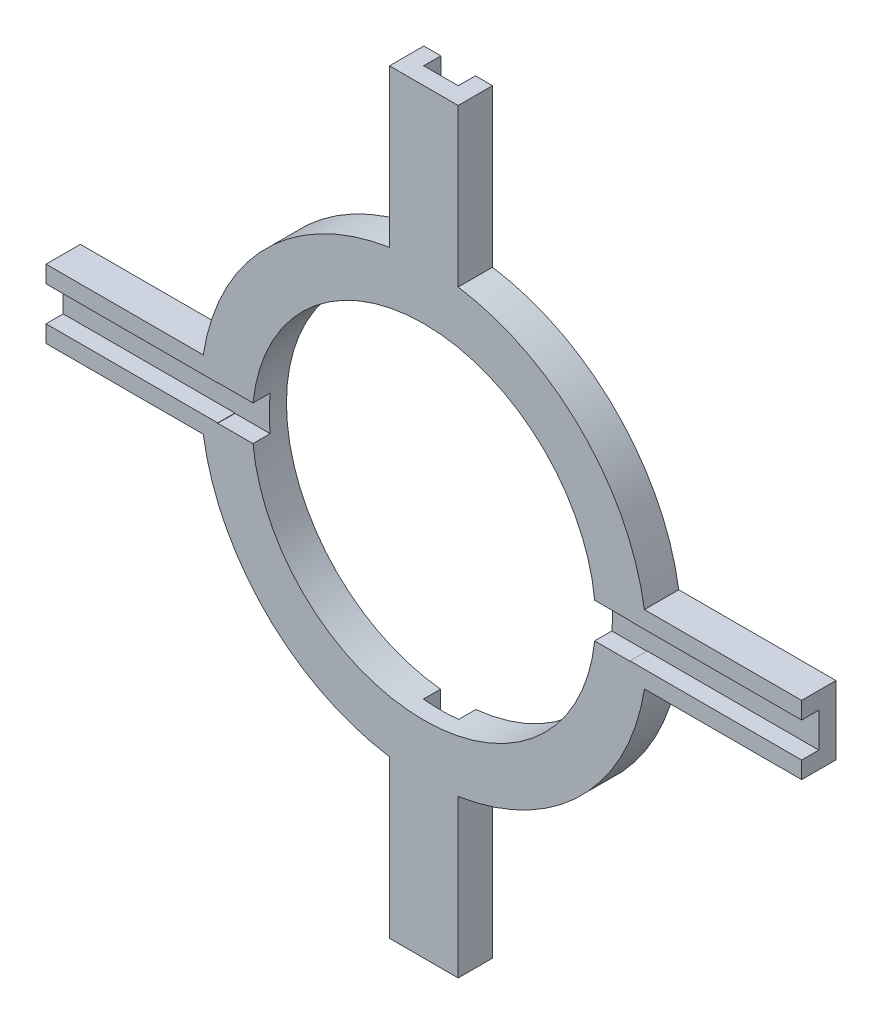
SolidWorks part; units mm, degrees
material "POM Acetal Copolymer"
ref_plane "Front Plane" through (0, 0, 0) normal (0, 0, 1) x (1, 0, 0)
ref_plane "Top Plane" through (0, 0, 0) normal (0, 1, 0) x (1, 0, 0)
ref_plane "Right Plane" through (0, 0, 0) normal (1, 0, 0) x (0, 0, -1)
sketch "Sketch1" plane through (0, 0, 0) normal (0, 0, 1) x (1, 0, 0)
  circle A0 centre (0, 0) radius 26
  circle A1 centre (0, 0) radius 20
extrude "Relieved_Floating_Ring" add sketch "Sketch1" along normal blind 4
sketch "Sketch2" plane through (0, 0, 0) normal (0, 0, 1) x (1, 0, 0)
  line L1 (-44, -4) -> (-24, -4)
  line L2 (-44, -4) -> (-44, 4)
  line L3 (-44, 4) -> (-24, 4)
  line L4 (-24, -4) -> (-24, 4)
extrude "X_Slide_Pad_-1" add sketch "Sketch2" along normal blind 4
sketch "Sketch3" plane through (0, 0, 0) normal (0, 0, 1) x (1, 0, 0)
  line L1 (-4, -44) -> (4, -44)
  line L2 (-4, -44) -> (-4, -24)
  line L3 (-4, -24) -> (4, -24)
  line L4 (4, -44) -> (4, -24)
extrude "Y_Slide_Pad_-1" add sketch "Sketch3" along normal blind 4
sketch "Sketch4" plane through (0, 0, 0) normal (0, 0, 1) x (1, 0, 0)
  line L1 (24, -4) -> (44, -4)
  line L2 (24, -4) -> (24, 4)
  line L3 (24, 4) -> (44, 4)
  line L4 (44, -4) -> (44, 4)
extrude "X_Slide_Pad_1" add sketch "Sketch4" along normal blind 4
sketch "Sketch5" plane through (0, 0, 0) normal (0, 0, 1) x (1, 0, 0)
  line L1 (-4, 24) -> (4, 24)
  line L2 (-4, 24) -> (-4, 44)
  line L3 (-4, 44) -> (4, 44)
  line L4 (4, 24) -> (4, 44)
extrude "Y_Slide_Pad_1" add sketch "Sketch5" along normal blind 4
sketch "Sketch6" plane through (0, 0, 0) normal (0, 0, -1) x (-1, 0, 0)
  line L0 (2.05, -45) -> (-2.05, -45)
  line L1 (-2.05, -45) -> (-2.05, 45)
  line L2 (-2.05, 45) -> (2.05, 45)
  line L3 (2.05, 45) -> (2.05, -45)
extrude "Lower_Y_Slots_W4p1_H2" cut sketch "Sketch6" against normal blind 2
sketch "Sketch7" plane through (0, 0, 4) normal (0, 0, 1) x (1, 0, 0)
  line L0 (-45, -2.05) -> (45, -2.05)
  line L1 (45, -2.05) -> (45, 2.05)
  line L2 (45, 2.05) -> (-45, 2.05)
  line L3 (-45, 2.05) -> (-45, -2.05)
extrude "Upper_X_Slots_W4p1_H2" cut sketch "Sketch7" against normal blind 2
sketch "Sketch8" plane through (0, 0, 0) normal (0, 0, 1) x (1, 0, 0)
  line L1 (-44, -2.06) -> (-24, -2.06)
  line L2 (-44, -2.06) -> (-44, -2.015)
  line L3 (-44, -2.015) -> (-24, -2.015)
  line L4 (-24, -2.06) -> (-24, -2.015)
extrude "Bench_UpperX_W4p030_-1_-1" add sketch "Sketch8" along normal blind 2 from offset 2
sketch "Sketch9" plane through (0, 0, 0) normal (0, 0, 1) x (1, 0, 0)
  line L1 (-44, 2.015) -> (-24, 2.015)
  line L2 (-44, 2.015) -> (-44, 2.06)
  line L3 (-44, 2.06) -> (-24, 2.06)
  line L4 (-24, 2.015) -> (-24, 2.06)
extrude "Bench_UpperX_W4p030_-1_1" add sketch "Sketch9" along normal blind 2 from offset 2
sketch "Sketch10" plane through (0, 0, 0) normal (0, 0, 1) x (1, 0, 0)
  line L1 (24, -2.06) -> (44, -2.06)
  line L2 (24, -2.06) -> (24, -2.015)
  line L3 (24, -2.015) -> (44, -2.015)
  line L4 (44, -2.06) -> (44, -2.015)
extrude "Bench_UpperX_W4p030_1_-1" add sketch "Sketch10" along normal blind 2 from offset 2
sketch "Sketch11" plane through (0, 0, 0) normal (0, 0, 1) x (1, 0, 0)
  line L1 (24, 2.015) -> (44, 2.015)
  line L2 (24, 2.015) -> (24, 2.06)
  line L3 (24, 2.06) -> (44, 2.06)
  line L4 (44, 2.015) -> (44, 2.06)
extrude "Bench_UpperX_W4p030_1_1" add sketch "Sketch11" along normal blind 2 from offset 2
sketch "Sketch12" plane through (0, 0, 0) normal (0, 0, 1) x (1, 0, 0)
  line L1 (-2.06, -44) -> (-2.015, -44)
  line L2 (-2.06, -44) -> (-2.06, -24)
  line L3 (-2.06, -24) -> (-2.015, -24)
  line L4 (-2.015, -44) -> (-2.015, -24)
extrude "Bench_LowerY_W4p030_-1_-1" add sketch "Sketch12" along normal blind 2
sketch "Sketch13" plane through (0, 0, 0) normal (0, 0, 1) x (1, 0, 0)
  line L1 (2.015, -44) -> (2.06, -44)
  line L2 (2.015, -44) -> (2.015, -24)
  line L3 (2.015, -24) -> (2.06, -24)
  line L4 (2.06, -44) -> (2.06, -24)
extrude "Bench_LowerY_W4p030_-1_1" add sketch "Sketch13" along normal blind 2
sketch "Sketch14" plane through (0, 0, 0) normal (0, 0, 1) x (1, 0, 0)
  line L1 (-2.06, 24) -> (-2.015, 24)
  line L2 (-2.06, 24) -> (-2.06, 44)
  line L3 (-2.06, 44) -> (-2.015, 44)
  line L4 (-2.015, 24) -> (-2.015, 44)
extrude "Bench_LowerY_W4p030_1_-1" add sketch "Sketch14" along normal blind 2
sketch "Sketch15" plane through (0, 0, 0) normal (0, 0, 1) x (1, 0, 0)
  line L1 (2.015, 24) -> (2.06, 24)
  line L2 (2.015, 24) -> (2.015, 44)
  line L3 (2.015, 44) -> (2.06, 44)
  line L4 (2.06, 24) -> (2.06, 44)
extrude "Bench_LowerY_W4p030_1_1" add sketch "Sketch15" along normal blind 2
